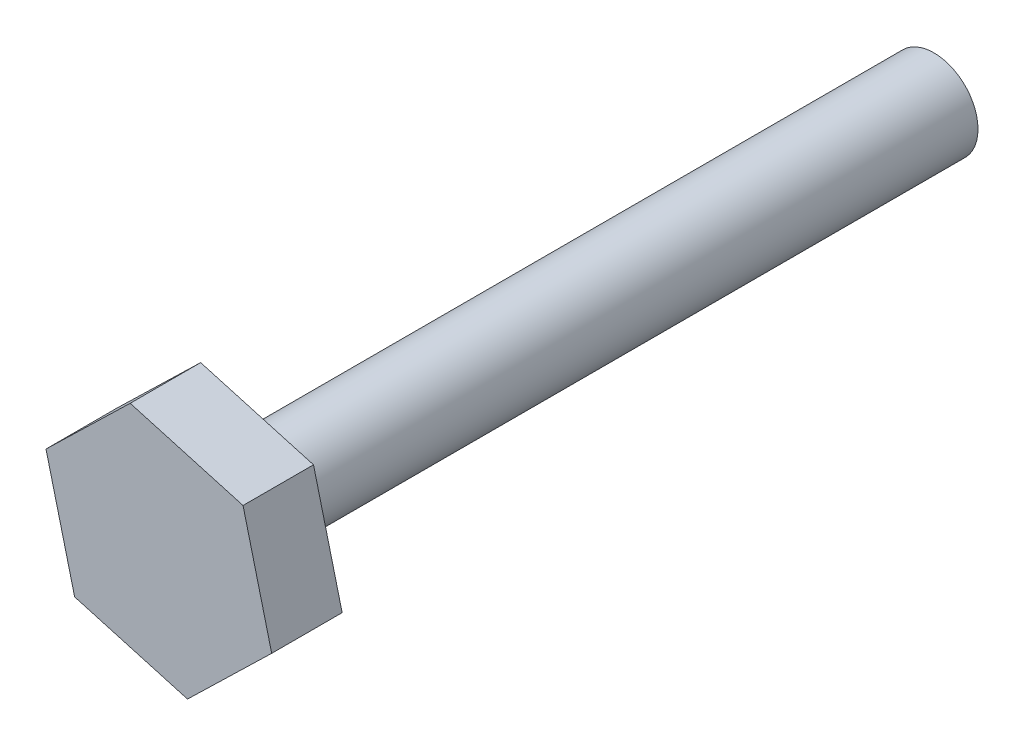
SolidWorks part; units mm, degrees
ref_plane "Спереди" through (0, 0, 0) normal (0, 0, 1) x (1, 0, 0)
ref_plane "Сверху" through (0, 0, 0) normal (0, 1, 0) x (1, 0, 0)
ref_plane "Справа" through (0, 0, 0) normal (1, 0, 0) x (0, 0, -1)
sketch "Эскиз1" plane through (0, 0, 0) normal (0, 0, 1) x (1, 0, 0)
  circle A0 centre (0, 0) radius 1.25
  dimension "D1" = 2.5
extrude "Бобышка-Вытянуть1" add sketch "Эскиз1" along normal blind 20
sketch "Эскиз3" plane through (0, 0, 20) normal (0, 0, 1) x (1, 0, 0)
  line L1 (2.3897, 2.3185) -> (-0.8131, 3.2288)
  line L2 (-0.8131, 3.2288) -> (-3.2028, 0.9103)
  line L3 (-3.2028, 0.9103) -> (-2.3897, -2.3185)
  line L4 (-2.3897, -2.3185) -> (0.8131, -3.2288)
  line L5 (0.8131, -3.2288) -> (3.2028, -0.9103)
  line L6 (3.2028, -0.9103) -> (2.3897, 2.3185)
  circle A0 centre (0, 0) radius 2.8835 construction
extrude "Бобышка-Вытянуть2" add sketch "Эскиз3" along normal blind 2
